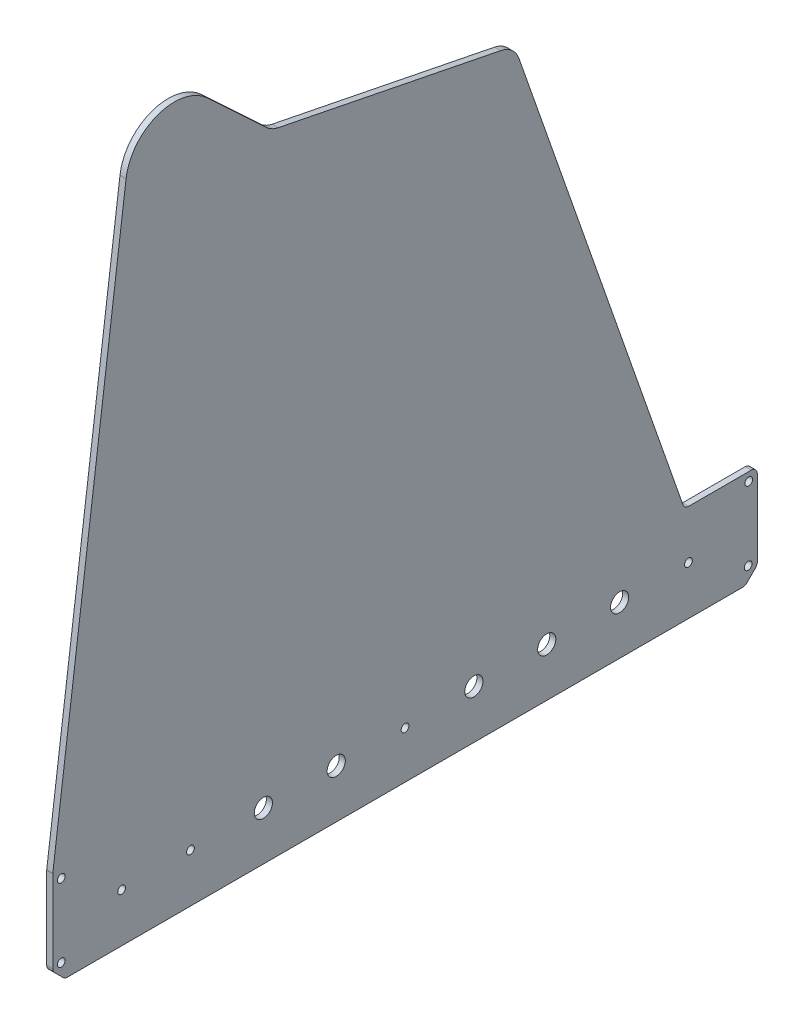
SolidWorks part; units mm, degrees
ref_plane "Front Plane" through (0, 0, 0) normal (0, 0, 1) x (1, 0, 0)
ref_plane "Top Plane" through (0, 0, 0) normal (0, 1, 0) x (1, 0, 0)
ref_plane "Right Plane" through (0, 0, 0) normal (1, 0, 0) x (0, 0, -1)
sketch "Sketch1" plane through (0, 0, 0) normal (1, 0, 0) x (0, 0, -1)
  line L0 (-184.15, -24.6062) -> (184.15, -24.6062)
  line L1 (184.15, -24.6062) -> (184.15, 26.1938)
  line L2 (184.15, 26.1938) -> (146.05, 26.1937)
  line L3 (146.05, 26.1937) -> (57.15, 280.1938)
  line L5 (-145.839, 321.5609) -> (-184.15, 26.1938)
  line L6 (-184.15, 26.1938) -> (-184.15, -24.6062)
  line L7 (-184.15, 350.0437) -> (184.15, 350.0437) construction
  line L8 (57.15, 280.1938) -> (-69.85, 305.5938)
  line L9 (-69.85, 305.5938) -> (-103.3099, 336.854)
  arc A0 (-103.3099, 336.854) -> (-145.839, 321.5609) centre (-120.65, 318.2937) ccw
  point P8 (0, -24.6062)
  dimension "D1" = 368.3
  dimension "D7" = 25.4
  dimension "D2" = 50.8
  dimension "D3" = 38.1
  dimension "D4" = 24.6062
  dimension "D5" = 374.65
  dimension "D6" = 304.8
  dimension "D8" = 342.9
  dimension "D9" = 127
  dimension "D10" = 304.8
  dimension "D11" = 25.4
  dimension "D12" = 127
extrude "Boss-Extrude1" add sketch "Sketch1" along normal blind 3.175
chamfer "Chamfer1" distance 6.35 angle 45 2 edges at (1.5875, -24.6062, 184.15) (1.5875, -24.6062, -184.15)
fillet "Fillet1" radius 12.7 2 edges at (1.5875, 305.5938, 69.85) (1.5875, 280.1938, -57.15)
sketch "Sketch2" plane through (0, 0, 0) normal (-1, 0, 0) x (0, 0, 1)
  point P0 (-112.1746, 0.7937)
  point P1 (-74.0746, 0.7937)
  point P3 (-35.9746, 0.7937)
  point P5 (74.0746, 0.7938)
  point P7 (35.9746, 0.7938)
hole_wizard "3/8 (0.375) Diameter Hole1" positions "Sketch5" profile "Sketch4" hole size "3/8" standard "ANSI Inch" end condition through all
sketch "Sketch5" plane through (0, 0, 0) normal (-1, 0, 0) x (0, 0, 1)
  point P0 (-112.1746, 0.7937)
  point P3 (-74.0746, 0.7937)
  point P6 (-35.9746, 0.7937)
  point P9 (35.9746, 0.7938)
  point P12 (74.0746, 0.7938)
sketch "Sketch4" plane through (0, 0.7937, -112.1746) normal (0, 1, 0) x (0, 0, 1)
  line L0 (0, 0) -> (0, 3.175)
  line L1 (0, 3.175) -> (4.7625, 3.175)
  line L2 (4.7625, 3.175) -> (4.7625, 0)
  line L5 (4.7625, 0) -> (0, 0)
  line L11 (0, -6.35) -> (0, 107.95) construction
  dimension "Thru Hole Dia." = 9.525
  dimension "Thru Hole Depth" = 3.175
sketch "Sketch6" plane through (0, 0, 0) normal (-1, 0, 0) x (0, 0, 1)
  line L0 (74.0746, 0.7938) -> (112.1746, 0.7938) construction
  line L1 (112.1746, 0.7938) -> (148.1579, 0.7938) construction
  line L2 (-112.1746, 0.7937) -> (-148.1579, 0.7937) construction
  line L3 (0, 0) -> (-35.9746, 0.7937) construction
  line L4 (74.0746, 0.7938) -> (35.9746, 0.7938) construction
  point P1 (112.1746, 0.7938)
  point P3 (148.1579, 0.7938)
  point P5 (-148.1579, 0.7937)
  point P7 (0, 0)
  point P17 (-148.1579, 0.7937)
  point P21 (0, 0)
  point P25 (112.1746, 0.7938)
  point P29 (148.1579, 0.7938)
hole_wizard "#8 Clearance Hole1" positions "Sketch6" profile "Sketch7" hole size "#8" standard "ANSI Inch" end condition through all
sketch "Sketch7" plane through (0, 0.7938, 148.1579) normal (0, 1, 0) x (0, 0, 1)
  line L0 (0, 0) -> (0, 3.175)
  line L1 (0, 3.175) -> (2.032, 3.175)
  line L2 (2.032, 3.175) -> (2.032, 0)
  line L5 (2.032, 0) -> (0, 0)
  line L11 (0, -6.35) -> (0, 107.95) construction
  dimension "Thru Hole Dia." = 4.064
  dimension "Thru Hole Depth" = 3.175
fillet "Fillet2" radius 3.175 3 edges at (1.5875, 26.1938, 184.15) (1.5875, 26.1938, -184.15) (1.5875, 26.1937, -146.05)
fillet "Fillet3" radius 3.175 4 edges at (1.5875, -18.2563, -184.15) (1.5875, -24.6062, -177.8) (1.5875, -18.2562, 184.15) (1.5875, -24.6062, 177.8)
hole_wizard "#8 Clearance Hole2" positions "Sketch12" profile "Sketch10" hole size "#8" standard "ANSI Inch" end condition through all
sketch "Sketch12" plane through (3.175, 0, 0) normal (1, 0, 0) x (0, 0, -1)
  point P0 (-179.705, 21.7488)
  point P3 (-179.705, -16.4151)
  point P7 (179.705, 21.7487)
  point P10 (179.3875, -16.2836)
sketch "Sketch10" plane through (3.175, 21.7488, 179.705) normal (0, 1, 0) x (0, 0, -1)
  line L0 (0, 0) -> (0, 3.175)
  line L1 (0, 3.175) -> (2.032, 3.175)
  line L2 (2.032, 3.175) -> (2.032, 0)
  line L5 (2.032, 0) -> (0, 0)
  line L11 (0, -6.35) -> (0, 107.95) construction
  dimension "Thru Hole Dia." = 4.064
  dimension "Thru Hole Depth" = 3.175
